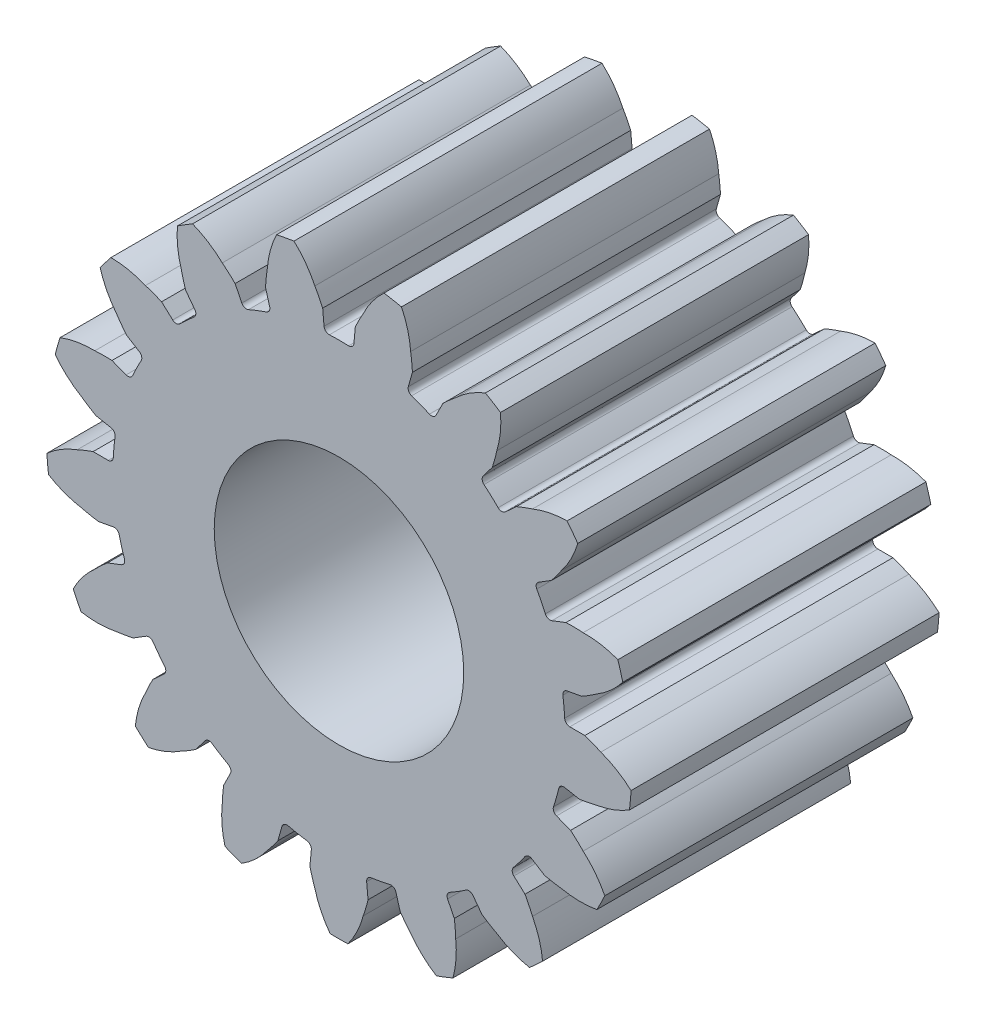
SolidWorks part; units mm, degrees
ref_plane "Plano frontal" through (0, 0, 0) normal (0, 0, 1) x (1, 0, 0)
ref_plane "Plano superior" through (0, 0, 0) normal (0, 1, 0) x (1, 0, 0)
ref_plane "Plano direito" through (0, 0, 0) normal (1, 0, 0) x (0, 0, -1)
sketch "Esboço1" plane through (0, 0, 0) normal (0, 0, 1) x (1, 0, 0)
  circle A0 centre (0, 0) radius 9.5
  dimension "D1" = 19
extrude "Ressalto-extrusão1" add sketch "Esboço1" along normal blind 10
sketch "Esboço2" plane through (0, 0, 10) normal (0, 0, 1) x (1, 0, 0)
  line L0 (0, 0) -> (0, 7.335) construction
  line L1 (0, 0) -> (0.7837, 8.4638) construction
  line L2 (0.5295, 7.9674) -> (0.4843, 7.4795)
  line L3 (-0.5295, 7.9674) -> (-0.4843, 7.4795)
  circle A0 centre (0, 0) radius 8.5 construction
  circle A1 centre (0, 0) radius 7.985 construction
  arc A2 (0.3113, 7.3284) -> (-0.3113, 7.3284) centre (0, 0) ccw
  arc A3 (0.7837, 8.4638) -> (1.4613, 9.3869) centre (3.5129, 7.1708) cw
  circle A4 centre (0, 0) radius 9.5 construction
  arc A5 (0.7837, 8.4638) -> (0.5295, 7.9674) centre (5.617, 5.6754) ccw
  arc A6 (-0.7837, 8.4638) -> (-0.5295, 7.9674) centre (-5.617, 5.6754) cw
  arc A7 (-0.7837, 8.4638) -> (-1.4613, 9.3869) centre (-3.5129, 7.1708) ccw
  arc A8 (1.4613, 9.3869) -> (-1.4613, 9.3869) centre (0, 0) ccw
  arc A9 (0.4843, 7.4795) -> (0.3113, 7.3284) centre (0.3183, 7.4949) cw
  arc A10 (-0.4843, 7.4795) -> (-0.3113, 7.3284) centre (-0.3183, 7.4949) ccw
  point P21 (0.4695, 7.32)
  point P24 (-0.4695, 7.32)
  dimension "D1" = 17
  dimension "D2" = 15.97
  dimension "D3" = 14.67
  dimension "D5" = 3.02
  dimension "D6" = 5.58
  dimension "D9" = 0.1667
  dimension "D4" = 5.29
  dimension "D7" = 5.29
extrude "Corte-extrusão2" cut sketch "Esboço2" against normal blind 10
pattern_circular "PadrãoCircular2" count 17 over 360 about axis through (0, 0, 0) along (0, 0, 1) of "Corte-extrusão2"
sketch "Esboço3" plane through (0, 0, 10) normal (0, 0, 1) x (1, 0, 0)
  circle A0 centre (0, 0) radius 4.05
  dimension "D1" = 8.1
extrude "Corte-extrusão3" cut sketch "Esboço3" against normal blind 10
